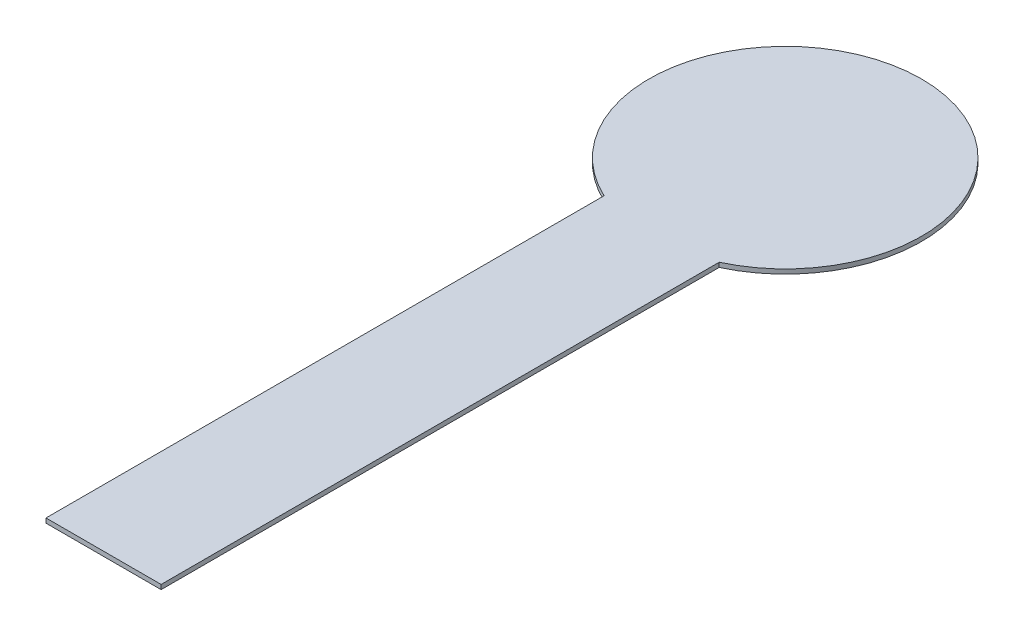
SolidWorks part; units mm, degrees
ref_plane "Front Plane" through (0, 0, 0) normal (0, 0, 1) x (1, 0, 0)
ref_plane "Top Plane" through (0, 0, 0) normal (0, 1, 0) x (1, 0, 0)
ref_plane "Right Plane" through (0, 0, 0) normal (1, 0, 0) x (0, 0, -1)
sketch "Sketch2" plane through (0, 0, 0) normal (0, 1, 0) x (1, 0, 0)
  line L6 (-3.8, -8.1584) -> (-3.8, -45)
  line L7 (-3.8, -45) -> (3.8, -45)
  line L8 (3.8, -8.1584) -> (3.8, -45)
  line L11 (-5.05, -8.9196) -> (-5.05, -46.25)
  line L12 (-5.05, -46.25) -> (5.05, -46.25)
  line L13 (5.05, -8.9196) -> (5.05, -46.25)
  arc A0 (3.8, -8.1584) -> (-3.8, -8.1584) centre (0, 0) ccw
  arc A2 (5.05, -8.9196) -> (-5.05, -8.9196) centre (0, 0) ccw
  point P8 (0, 0)
  dimension "D1" = 18
  dimension "D2" = 18
  dimension "D3" = 18
  dimension "D5" = 7.6
  dimension "D6" = 1.25
extrude "Boss-Extrude1" add sketch "Sketch2" against normal blind 0.3 contours A0 L6 L7 L8
